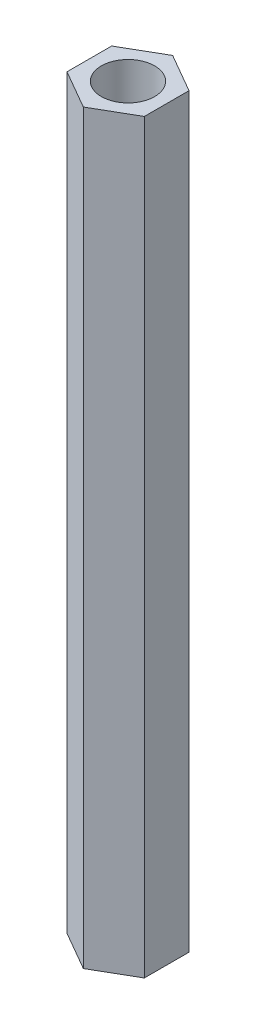
SolidWorks part; units mm, degrees
material "黄铜"
ref_plane "前视基准面" through (0, 0, 0) normal (0, 0, 1) x (1, 0, 0)
ref_plane "上视基准面" through (0, 0, 0) normal (0, 1, 0) x (1, 0, 0)
ref_plane "右视基准面" through (0, 0, 0) normal (1, 0, 0) x (0, 0, -1)
sketch "草图1" plane through (0, 0, 0) normal (0, 1, 0) x (1, 0, 0)
  line L0 (0, 2.5139) -> (-2.1771, 1.257)
  line L1 (-2.1771, 1.257) -> (-2.1771, -1.257)
  line L2 (-2.1771, -1.257) -> (0, -2.5139)
  line L3 (0, -2.5139) -> (2.1771, -1.257)
  line L4 (2.1771, -1.257) -> (2.1771, 1.257)
  line L5 (2.1771, 1.257) -> (0, 2.5139)
  circle A0 centre (0, 0) radius 1.5
extrude "凸台-拉伸1" add sketch "草图1" along normal blind 42
